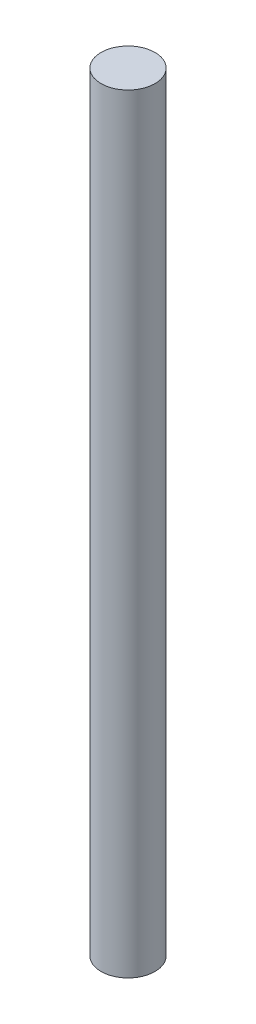
SolidWorks part; units mm, degrees
material "ABS"
ref_plane "正面" through (0, 0, 0) normal (0, 0, 1) x (1, 0, 0)
ref_plane "平面" through (0, 0, 0) normal (0, 1, 0) x (1, 0, 0)
ref_plane "右側面" through (0, 0, 0) normal (1, 0, 0) x (0, 0, -1)
sketch "ｽｹｯﾁ1" plane through (0, 0, 0) normal (0, 1, 0) x (1, 0, 0)
  circle A0 centre (0, 0) radius 1
  dimension "D1" = 2
extrude "ﾎﾞｽ - 押し出し1" add sketch "ｽｹｯﾁ1" along normal blind 28.5
